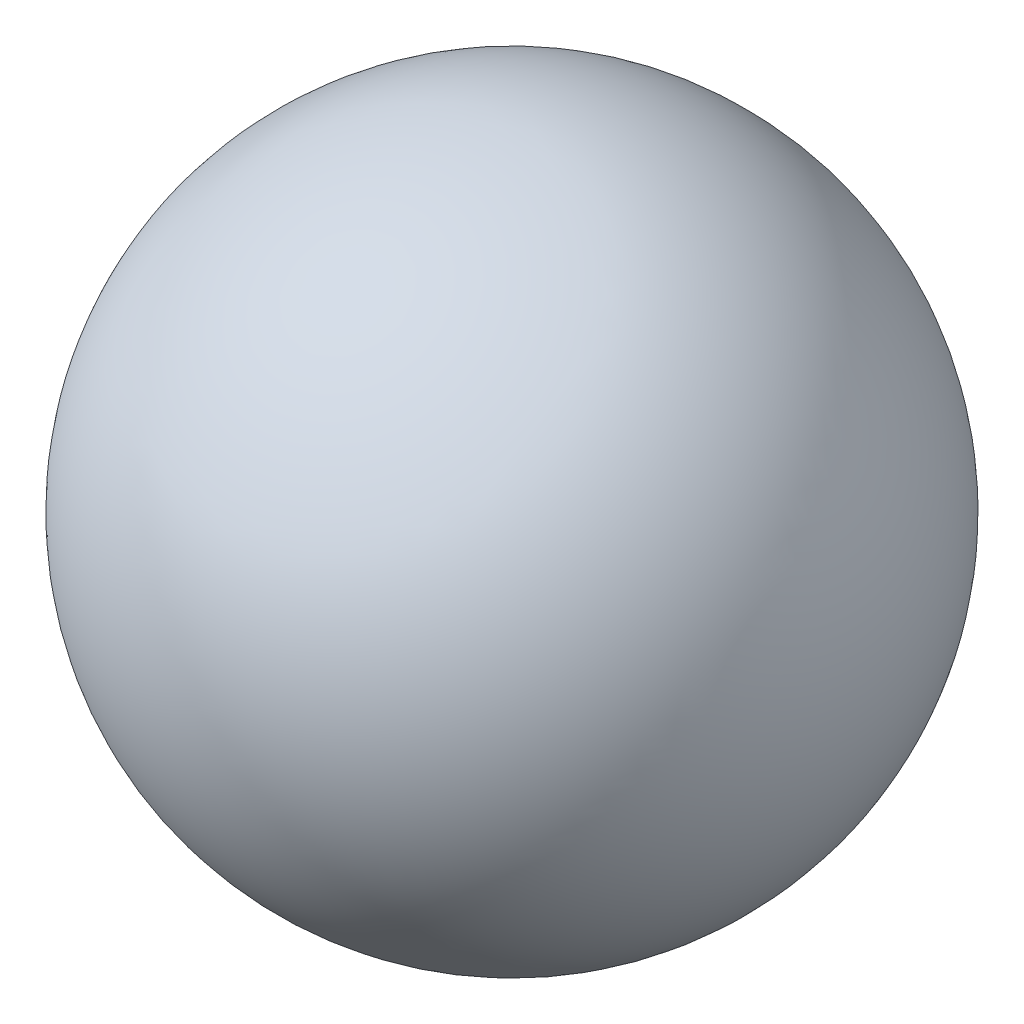
SolidWorks part; units mm, degrees
ref_plane "Front Plane" through (0, 0, 0) normal (0, 0, 1) x (1, 0, 0)
ref_plane "Top Plane" through (0, 0, 0) normal (0, 1, 0) x (1, 0, 0)
ref_plane "Right Plane" through (0, 0, 0) normal (1, 0, 0) x (0, 0, -1)
ref_plane "Plane1" through (0, 0, 0) normal (0, 0, 1) x (1, 0, 0)
sketch "Sketch1" plane through (0, 0, 0) normal (0, 0, 1) x (1, 0, 0)
  line L0 (2.1, 2.95) -> (0.9, 2.95)
  line L1 (2.1, 2.95) -> (0.9, 2.95) construction
  arc A0 (0.9, 2.95) -> (2.1, 2.95) centre (1.5, 2.95) cw
revolve "Revolve1" add sketch "Sketch1" angle 360 about L1
